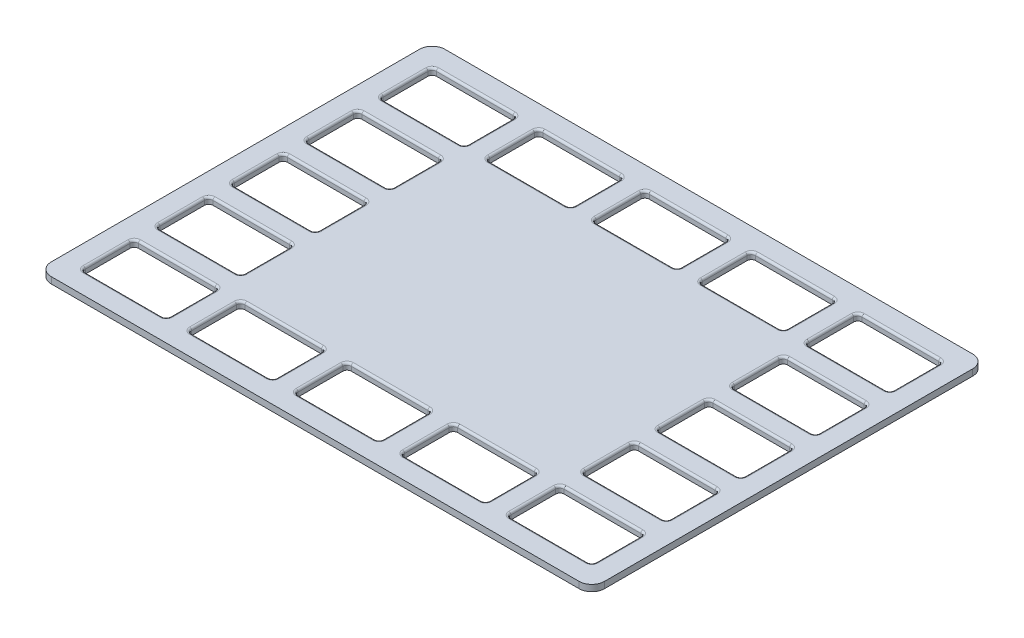
SolidWorks part; units mm, degrees
ref_plane "Front" through (0, 0, 0) normal (0, 0, 1) x (1, 0, 0)
ref_plane "Top" through (0, 0, 0) normal (0, 1, 0) x (1, 0, 0)
ref_plane "Right" through (0, 0, 0) normal (1, 0, 0) x (0, 0, -1)
sketch "Sketch1" plane through (0, 0, 0) normal (0, 1, 0) x (1, 0, 0)
  line L1 (0, 0) -> (260, 0)
  line L2 (0, 0) -> (0, 185)
  line L3 (0, 185) -> (260, 185)
  line L4 (260, 0) -> (260, 185)
  dimension "D1" = 260
  dimension "D2" = 185
extrude "Extrude1" add sketch "Sketch1" along normal blind 3
fillet "Fillet3" radius 6 4 edges at (0, 1.5, -185) (260, 1.5, -185) (260, 1.5, 0) (0, 1.5, 0)
sketch "Sketch2" plane through (0, 3, 0) normal (0, 1, 0) x (-1, 0, 0)
  line L0 (0, -179) -> (0, -6) construction
  line L1 (-10, -10) -> (-50, -10)
  line L2 (-10, -10) -> (-10, -35)
  line L3 (-10, -35) -> (-50, -35)
  line L4 (-50, -10) -> (-50, -35)
  line L5 (-6, 0) -> (-254, 0) construction
  dimension "D1" = 10
  dimension "D2" = 10
  dimension "D3" = 40
  dimension "D4" = 25
extrude "Cut-Extrude1" cut sketch "Sketch2" against normal through all
fillet "Fillet1" radius 2 4 edges at (50, 1.5, -35) (50, 1.5, -10) (10, 1.5, -10) (10, 1.5, -35)
fillet "Fillet2" radius 1 8 edges at (10.5858, 3, -10.5858) (10, 3, -22.5) (10.5858, 3, -34.4142) (30, 3, -35) (49.4142, 3, -34.4142) (50, 3, -22.5) (49.4142, 3, -10.5858) (30, 3, -10)
pattern_linear "直線複製排列1" count 5 spacing 50 along (1, 0, 0) count 5 spacing 35 along (0, 0, -1) skipping (1, 1), (1, 2), (1, 3), (2, 1), (2, 2), (2, 3), (3, 1), (3, 2), (3, 3) of "Cut-Extrude1", "Fillet1", "Fillet2"
